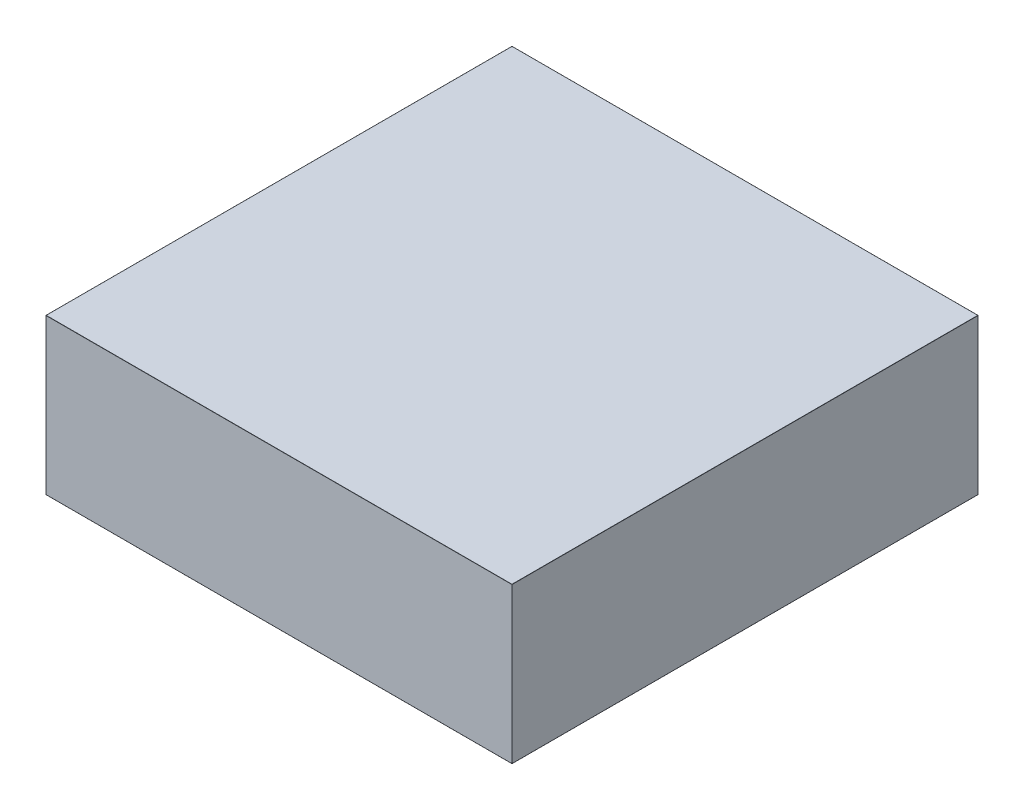
SolidWorks part; units mm, degrees
ref_plane "Front Plane" through (0, 0, 0) normal (0, 0, 1) x (1, 0, 0)
ref_plane "Top Plane" through (0, 0, 0) normal (0, 1, 0) x (1, 0, 0)
ref_plane "Right Plane" through (0, 0, 0) normal (1, 0, 0) x (0, 0, -1)
sketch "Sketch1" plane through (0, 0, 0) normal (0, 0, 1) x (1, 0, 0)
  line L1 (-150, -50) -> (150, -50)
  line L2 (-150, -50) -> (-150, 50)
  line L3 (-150, 50) -> (150, 50)
  line L4 (150, -50) -> (150, 50)
  line L5 (-150, -50) -> (150, 50) construction
  line L6 (-150, 50) -> (150, -50) construction
  point P0 (0, 0)
  dimension "D1" = 100
  dimension "D2" = 300
extrude "Boss-Extrude1" add sketch "Sketch1" along normal mid plane 300
fillet "Fillet1" radius 0.1 12 edges at (-150, 0, -150) (-150, -50, 0) (0, -50, -150) (150, -50, 0) (150, 0, -150) (0, -50, 150) (-150, 0, 150) (150, 0, 150) (150, 50, 0) (0, 50, 150) (-150, 50, 0) (0, 50, -150)
